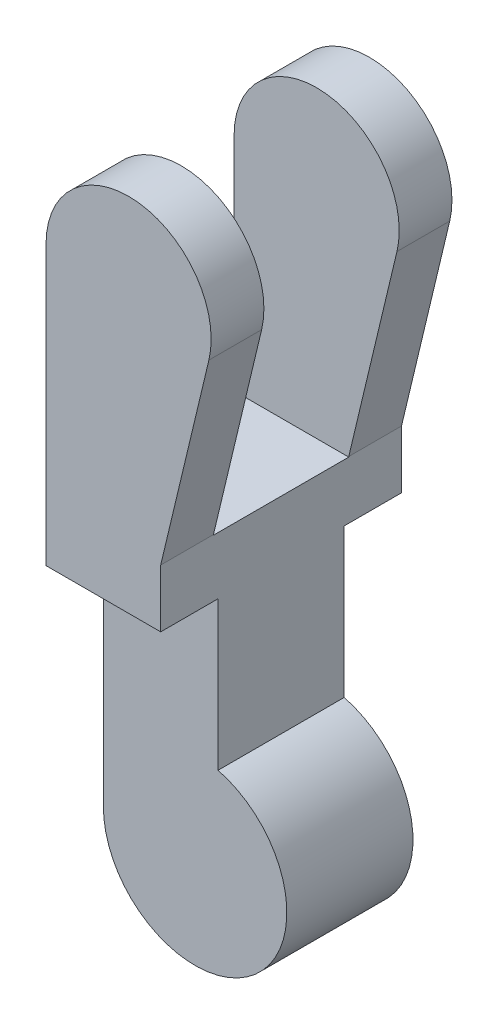
SolidWorks part; units mm, degrees
ref_plane "Front Plane" through (0, 0, 0) normal (0, 0, 1) x (1, 0, 0)
ref_plane "Top Plane" through (0, 0, 0) normal (0, 1, 0) x (1, 0, 0)
ref_plane "Right Plane" through (0, 0, 0) normal (1, 0, 0) x (0, 0, -1)
sketch "Sketch1" plane through (0, 0, 0) normal (0, 0, 1) x (1, 0, 0)
  line L0 (-80, 0) -> (-80, 450)
  line L1 (20, 77.4597) -> (20, 257.4597)
  line L2 (20, 257.4597) -> (62.0268, 433.2594)
  arc A0 (-80, 0) -> (20, 77.4597) centre (0, 0) ccw
  arc A1 (62.0268, 433.2594) -> (-80, 450) centre (-8, 450) ccw
  dimension "D1" = 160
  dimension "D2" = 144
  dimension "D3" = 100
  dimension "D4" = 180
  dimension "D5" = 450
extrude "Boss-Extrude1" add sketch "Sketch1" along normal mid plane 210
sketch "Sketch2" plane through (0, 0, 0) normal (1, 0, 0) x (0, 0, -1)
  line L0 (105, 522) -> (-105, 522) construction
  line L1 (-59, 522) -> (59, 522)
  line L2 (-59, 522) -> (-59, 257)
  line L3 (-59, 257) -> (59, 257)
  line L4 (59, 522) -> (59, 257)
  line L5 (0, 522) -> (0, -157.5108) construction
  line L6 (0, 261.25) -> (0, -261.25) construction
  line L7 (-105, 77.4597) -> (-105, 257.4597) construction
  line L8 (-105, 207) -> (-55, 207)
  line L9 (-105, 207) -> (-105, -80)
  line L10 (-105, -80) -> (-55, -80)
  line L11 (-55, 207) -> (-55, -80)
  line L12 (-105, -80) -> (105, -80) construction
  line L13 (105, -80) -> (55, -80)
  line L14 (55, 207) -> (55, -80)
  line L15 (105, 207) -> (55, 207)
  line L16 (105, 207) -> (105, -80)
  point P6 (0, 257)
  dimension "D1" = 265
  dimension "D2" = 118
  dimension "D3" = 287
  dimension "D4" = 50
extrude "Cut-Extrude1" cut sketch "Sketch2" against normal through all both and the other way through all
